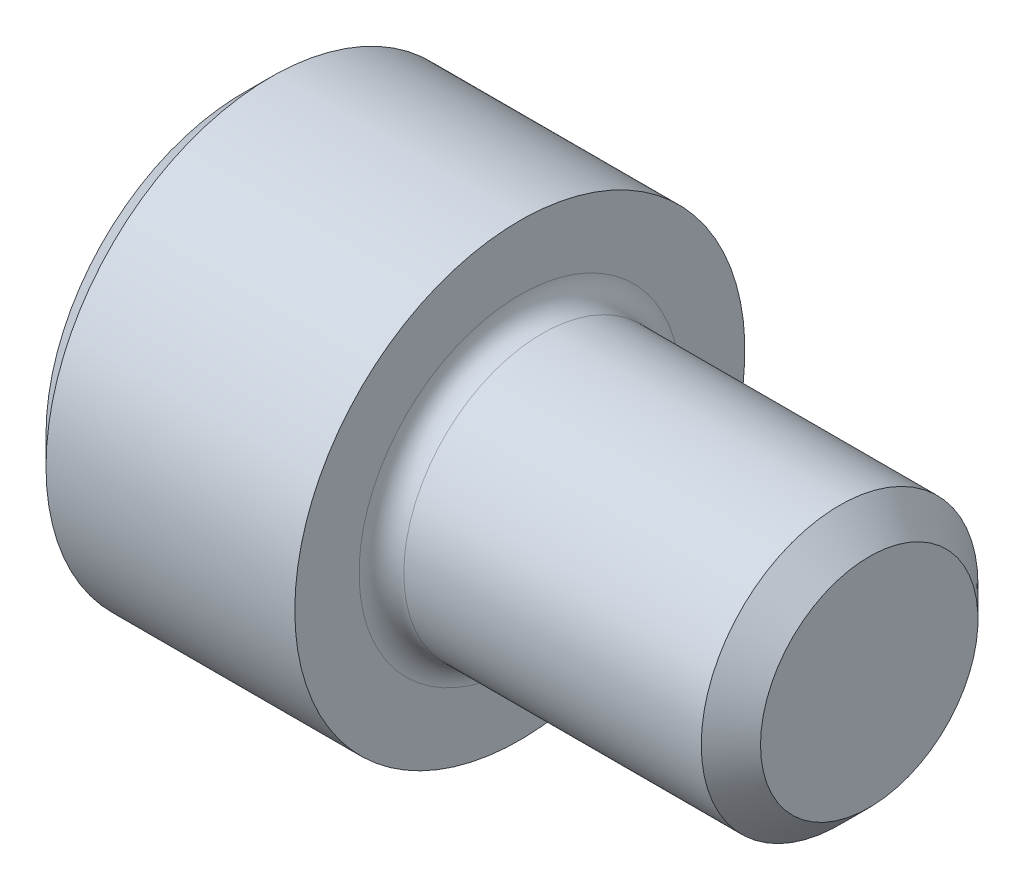
SolidWorks part; units mm, degrees
revolve "Base-Revolve" add sketch "BodySke"
sketch "BodySke" plane through (0, 0, 0) normal (0, 0, 1) x (1, 0, 0)
  line L0 (0, 0) -> (0, 1.7907)
  line L1 (0.254, 2.0447) -> (2.5146, 2.0447)
  line L2 (2.5146, 2.0447) -> (2.5146, 1.2573)
  line L3 (2.5146, 1.2573) -> (5.4204, 1.2573)
  line L4 (5.6896, 0.9881) -> (5.6896, 0)
  line L5 (5.6896, 0) -> (0, 0)
  line L6 (-31.75, 0) -> (127, 0) construction
  line L7 (0, 1.7907) -> (0.254, 2.0447)
  line L8 (5.6896, 0.9881) -> (5.4204, 1.2573)
  line L9 (0, -1.7907) -> (0.254, -2.0447) construction
  line L10 (5.6896, -0.9881) -> (5.4204, -1.2573) construction
  line L11 (2.9693, 9.525) -> (2.9693, 3.175) construction
  line L12 (2.5146, 9.525) -> (2.5146, 3.175) construction
  line L13 (-32.4104, 9.525) -> (-32.4104, 3.175) construction
  dimension "Diameter" = 2.5146
  dimension "Head_ht" = 2.5146
  dimension "Length" = 3.175
  dimension "Body_ch_ang" = 45
  dimension "Head_dia" = 4.0894
  dimension "Head_ch_ang" = 45
  dimension "Head_side_ht" = 2.2606
  dimension "Minor_dia" = 1.9761
  dimension "Advance" = 0.4547
  dimension "Thread_nom" = 3.175
  dimension "Thread_length" = 38.1
cosmetic thread "ThreadCosmetic" [suppressed]
fillet "Fillet1" radius 0.2032 1 edges at (2.5146, 0, 1.2573)
ref_plane "Plane1" through (0, 0, 0) normal (0, 0, 1) x (1, 0, 0)
ref_plane "Plane2" through (0, 0, 0) normal (0, 1, 0) x (1, 0, 0)
ref_plane "Plane3" through (0, 0, 0) normal (1, 0, 0) x (0, 0, -1)
other "Configuration Table"
sketch "Sketch2" plane through (0, 0, 0) normal (0, 0, 1) x (1, 0, 0)
  line L0 (0, 0.9906) -> (1.1176, 0.9906)
  line L1 (1.1176, 0.9906) -> (1.6895, 0)
  line L2 (-31.75, 0) -> (127, 0) construction
  line L3 (1.6895, 0) -> (0, 0)
  line L4 (0, 0) -> (0, 0.9906)
  line L5 (0, 1.7907) -> (0, -1.7907) construction
  line L6 (0, 0) -> (47.625, 0) construction
  line L7 (2.5146, -2.0447) -> (2.5146, 2.0447) construction
  dimension "D1" = 0.9906
  dimension "D2" = 60
revolve "Hex-PreBroach" cut sketch "Sketch2" angle 360 about L6
sketch "Sketch3" plane through (0, 0, 0) normal (-1, 0, 0) x (0, 0.5, 0.866)
  line L0 (0.5719, 0.9906) -> (-0.5719, 0.9906)
  line L1 (-0.5719, 0.9906) -> (-1.1438, 0)
  line L2 (0.5719, 0.9906) -> (1.1438, 0)
  line L3 (0.5719, -0.9906) -> (1.1438, 0)
  line L4 (0.5719, -0.9906) -> (-0.5719, -0.9906)
  line L5 (-0.5719, -0.9906) -> (-1.1438, 0)
  dimension "D1" = 0.9906
  dimension "D2" = 0.9906
  dimension "Hex_size" = 1.9812
extrude "Hex" cut sketch "Sketch3" against normal blind 1.1176
sketch "Sketch4" plane through (0, 0, 0) normal (-1, 0, 0) x (0, 0, 1)
  line L0 (0, 0) -> (1.2446, 0)
  line L1 (0, 0) -> (6.1484, 3.5498) construction
  line L2 (0, 0) -> (0.6223, 1.0779)
  line L3 (1.0085, 0.2596) -> (1.19, 0.3644)
  line L4 (0.7291, 0.7436) -> (0.9106, 0.8484)
  arc A0 (1.0085, 0.2596) -> (0.7291, 0.7436) centre (0, 0) ccw
  arc A1 (1.2446, 0) -> (1.19, 0.3644) centre (0, 0) ccw
  arc A2 (0.6223, 1.0779) -> (0.9106, 0.8484) centre (0, 0) cw
  dimension "D1" = 30
  dimension "D2" = 60
  dimension "Spline_p_dim" = 0.5588
  dimension "D3" = 0.2794
extrude "Spline" [suppressed] cut sketch "Sketch4" against normal blind 1.1176
pattern_circular "CirPattern1" [suppressed] count 6 every 60
sketch "Sketch5" plane through (0, 0, 0) normal (0, 0, 1) x (1, 0, 0)
  line L0 (-31.75, 0) -> (127, 0) construction
  line L2 (0, 1.7907) -> (0, -1.7907) construction
  circle A0 centre (0.254, 0) radius 0.0127
  dimension "Drilled_hole_dia" = 0.0254
  dimension "Drilled_hole_loc" = 0.254
extrude "Hole" [suppressed] cut sketch "Sketch5" against normal through all and the other way through all
pattern_circular "Drilled-4" [suppressed] count 2 every 60
pattern_circular "Drilled-6" [suppressed] count 3 every 60
sketch "ThdSchSke" plane through (0, 0, 0) normal (0, 0, 1) x (1, 0, 0)
  line L0 (2.9693, -0.9881) -> (2.7807, -1.2573)
  line L1 (2.9693, -0.9881) -> (3.1578, -1.2573)
  line L2 (3.1578, -1.2573) -> (3.1578, -1.5716)
  line L3 (-3.175, 0) -> (5.1513, 0) construction
  line L5 (3.1578, -1.5716) -> (2.7807, -1.5716)
  line L6 (2.7807, -1.5716) -> (2.7807, -1.2573)
  line L7 (0, 1.7907) -> (0, -1.7907) construction
  dimension "Thread_minor" = 1.9761
  dimension "Diameter" = 2.5146
  dimension "Start" = 2.9693
revolve "ThreadSchematic" [suppressed] cut sketch "ThdSchSke" angle 360 about L3
pattern_linear "ThdSchPat" [suppressed]
equation "\"D2@Sketch3\" = \"Hex_size@Sketch3\" / 2"
equation "\"D1@Sketch3\" = \"Hex_size@Sketch3\" / 2"
equation "\"D1@Sketch2\" = \"Hex_size@Sketch3\" / 2"
equation "\"D3@Sketch4\" = \"Spline_p_dim@Sketch4\" / 2"
equation "\"Thread_minor@ThreadCosmetic\"  =  \"Minor_dia@BodySke\""
equation "\"D2@CirPattern1\" = 360 / \"Num_teeth@CirPattern1\""
equation "\"Wall_thickness@Sketch2\" = \"Head_ht@BodySke\" - \"Key_eng@Hex\""
equation "\"Thread_length@ThreadCosmetic\" = ((sgn( (\"Length@BodySke\" - \"Advance@BodySke\" ) - \"Thread_nom@BodySke\" )-1)*( (\"Length@BodySke\" - \"Advance@BodySke\" ) - \"Thread_nom@BodySke\" ))/-2+ \"Thread_nom@BodySke\""
equation "\"Thread_minor@ThdSchSke\" = \"Minor_dia@BodySke\""
equation "\"Diameter@ThdSchSke\" = \"Diameter@BodySke\""
equation "\"Overcut@ThdSchSke\" = \"Diameter@BodySke\" * 1.25"
equation "\"Start@ThdSchSke\" = \"Head_ht@BodySke\" + \"Length@BodySke\" - \"Thread_length@ThreadCosmetic\"  '---Non-countersunk---"
equation "\"Num_threads@ThdSchPat\" = int( \"Thread_length@ThreadCosmetic\" / \"Advance@BodySke\" + 0.999 )  + 1"
equation "\"Advance@ThdSchPat\" = \"Thread_length@ThreadCosmetic\" /  (\"Num_threads@ThdSchPat\" - 1) 'relax it"
equation "\"Num_threads@ThdSchPat\" = \"Num_threads@ThdSchPat\" - sgn( \"Num_threads@ThdSchPat\" - 1) '---chamfered tips only---"
